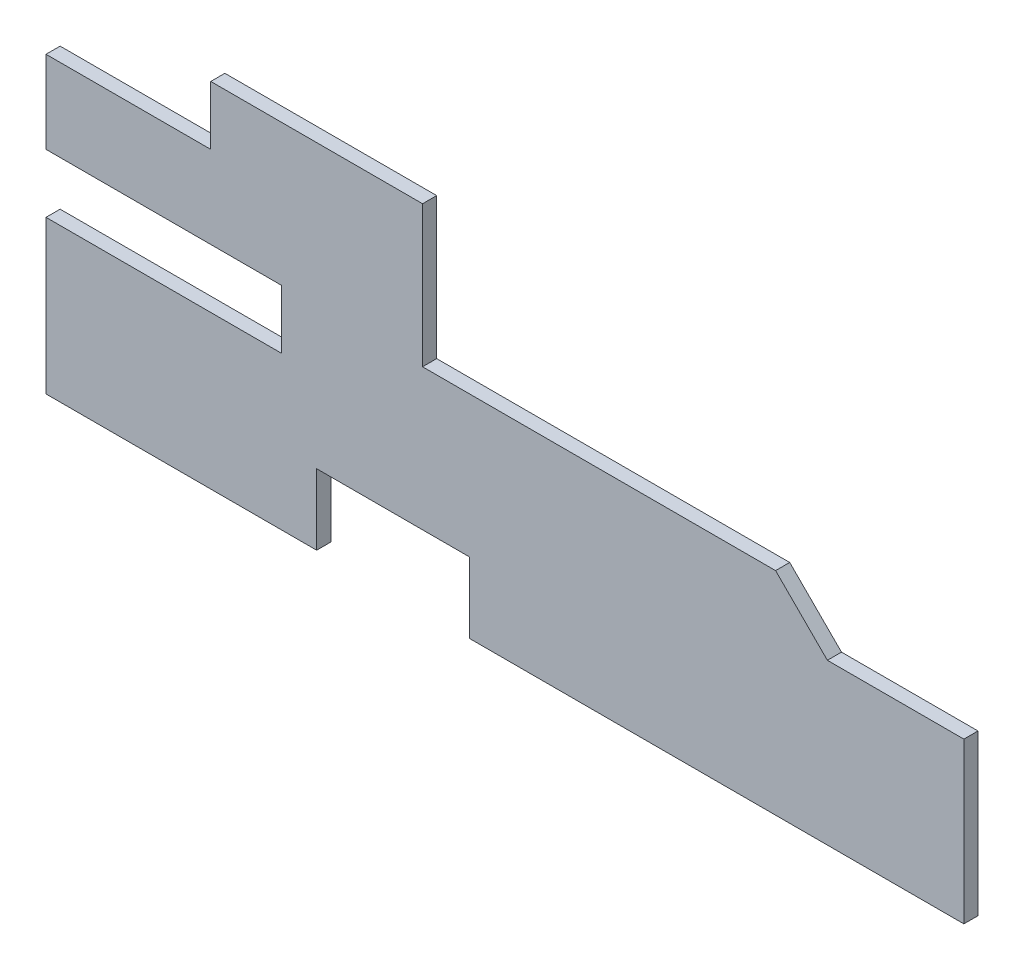
SolidWorks part; units mm, degrees
material "铜"
ref_plane "前视基准面" through (0, 0, 0) normal (0, 0, 1) x (1, 0, 0)
ref_plane "上视基准面" through (0, 0, 0) normal (0, 1, 0) x (1, 0, 0)
ref_plane "右视基准面" through (0, 0, 0) normal (1, 0, 0) x (0, 0, -1)
sketch "草图1" plane through (0, 0, 0) normal (0, 0, 1) x (1, 0, 0)
  line L0 (0, 0) -> (11.5, 0)
  line L1 (11.5, 0) -> (11.5, 3)
  line L2 (11.5, 3) -> (18, 3)
  line L3 (18, 3) -> (18, 0)
  line L4 (18, 0) -> (39, 0)
  line L5 (39, 0) -> (39, 6.8)
  line L6 (39, 6.8) -> (33.2, 6.8)
  line L7 (33.2, 6.8) -> (31, 9)
  line L8 (31, 9) -> (16, 9)
  line L9 (16, 9) -> (16, 15)
  line L10 (16, 15) -> (7, 15)
  line L11 (7, 15) -> (7, 12.5)
  line L12 (7, 12.5) -> (0, 12.5)
  line L13 (0, 12.5) -> (0, 9)
  line L14 (0, 9) -> (10, 9)
  line L15 (10, 9) -> (10, 6.5)
  line L16 (10, 6.5) -> (0, 6.5)
  line L17 (0, 6.5) -> (0, 0)
  dimension "D1" = 39
  dimension "D2" = 15
  dimension "D3" = 16
  dimension "D4" = 9
  dimension "D5" = 15
  dimension "D6" = 6.8
  dimension "D7" = 6.5
  dimension "D8" = 11.5
  dimension "D9" = 10
  dimension "D10" = 2.5
  dimension "D11" = 6.5
  dimension "D12" = 3.5
  dimension "D13" = 3
  dimension "D14" = 7
  dimension "D15" = 2.2
extrude "凸台-拉伸1" add sketch "草图1" along normal blind 0.6
